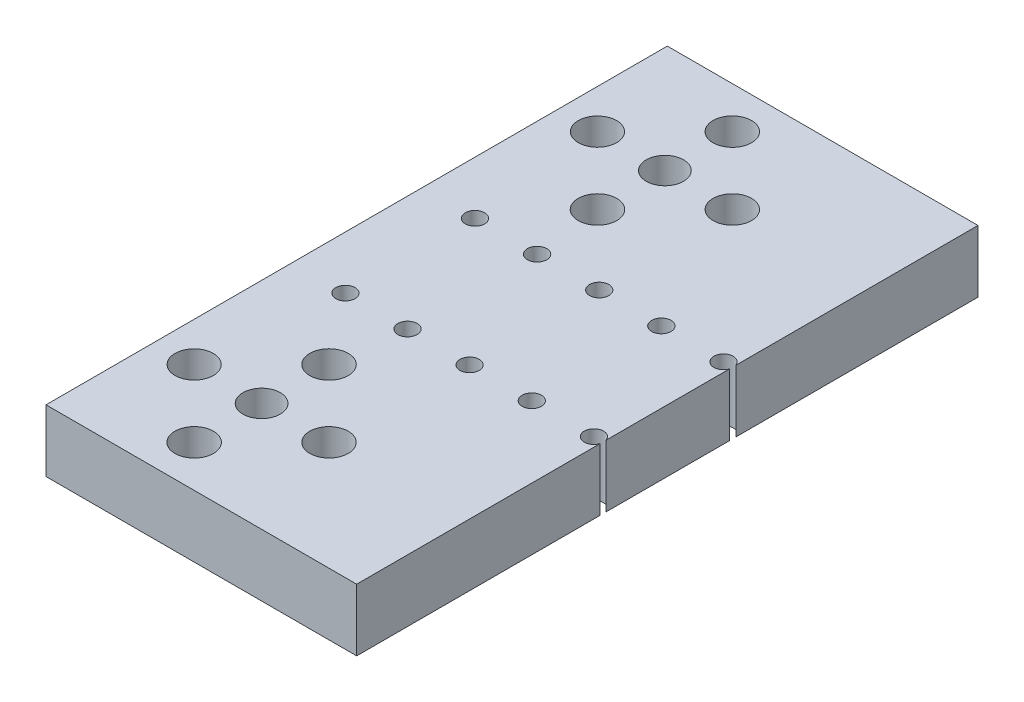
SolidWorks part; units mm, degrees
ref_plane "Front Plane" through (0, 0, 0) normal (0, 0, 1) x (1, 0, 0)
ref_plane "Top Plane" through (0, 0, 0) normal (0, 1, 0) x (1, 0, 0)
ref_plane "Right Plane" through (0, 0, 0) normal (1, 0, 0) x (0, 0, -1)
sketch "Sketch1" plane through (0, 0, 0) normal (0, 1, 0) x (1, 0, 0)
  line L1 (0, -50) -> (-50, -50)
  line L2 (0, -50) -> (0, 50)
  line L3 (0, 50) -> (-50, 50)
  line L4 (-50, -50) -> (-50, 50)
  point P0 (0, 0)
  dimension "D1" = 100
  dimension "D2" = 50
extrude "Boss-Extrude1" add sketch "Sketch1" along normal blind 10
sketch "Sketch2" plane through (0, 10, 0) normal (0, 1, 0) x (1, 0, 0)
  line L0 (0, 0) -> (-8.3656, 0) construction
  circle A0 centre (-32.8473, -43.3054) radius 3.1044
  circle A1 centre (-43.6988, -32.4539) radius 3.0852
  circle A2 centre (-21.9958, -32.4539) radius 3.1
  circle A3 centre (-32.8473, -21.6024) radius 3.1044
  circle A4 centre (-32.8473, -32.4539) radius 3.0045
  circle A5 centre (-32.8473, 32.4539) radius 3.0045
  circle A6 centre (-32.8473, 21.6024) radius 3.1044
  circle A7 centre (-21.9958, 32.4539) radius 3.1
  circle A8 centre (-43.6988, 32.4539) radius 3.0852
  circle A9 centre (-32.8473, 43.3054) radius 3.1044
extrude "Cut-Extrude1" cut sketch "Sketch2" against normal through all both and the other way through all
sketch "Sketch4" plane through (0, 10, 0) normal (0, 1, 0) x (1, 0, 0)
  line L0 (-50, -50) -> (-50, 50) construction
  line L1 (-50, 50) -> (-50, 0) construction
  line L2 (-50, 0) -> (-33.8678, 0) construction
  circle A0 centre (-41.4744, -10.3435) radius 1.55
  circle A2 centre (-21.4744, -10.3435) radius 1.55
  circle A4 centre (-41.4744, 10.5152) radius 1.5574
  circle A5 centre (-21.4744, 10.5152) radius 1.55
  circle A6 centre (-31.4744, -10.3435) radius 1.55
  circle A7 centre (-31.4744, 10.5152) radius 1.5574
  circle A8 centre (-21.4744, -10.3435) radius 1.55
  circle A9 centre (-21.4744, 10.5152) radius 1.5574
  circle A10 centre (-11.4744, -10.3435) radius 1.55
  circle A11 centre (-11.4744, 10.5152) radius 1.5574
  circle A12 centre (-1.4744, -10.3435) radius 1.55
  circle A13 centre (-1.4744, 10.5152) radius 1.5574
  dimension "D1" = 2
  dimension "D2" = 5
extrude "Cut-Extrude2" cut sketch "Sketch4" against normal through all both and the other way through all contours A4 | A0 | A6 | A7 | A5 | A2 | A10 | A12 | A11 | A13
